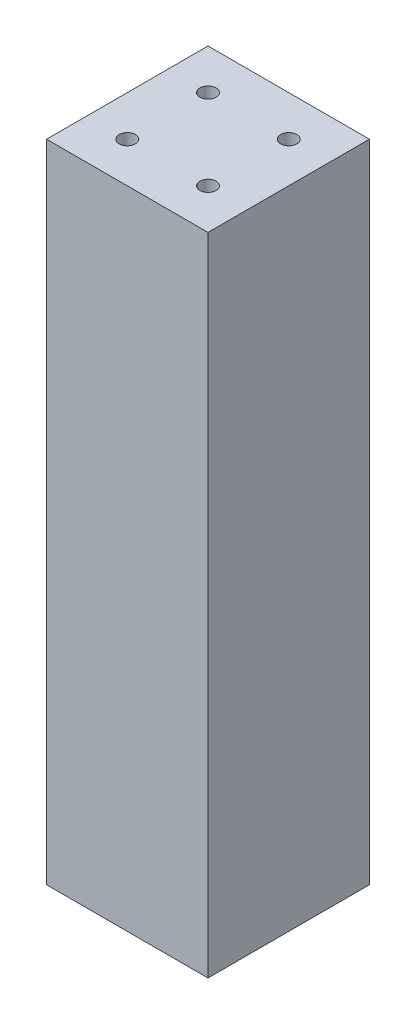
SolidWorks part; units mm, degrees
ref_plane "Front Plane" through (0, 0, 0) normal (0, 0, 1) x (1, 0, 0)
ref_plane "Top Plane" through (0, 0, 0) normal (0, 1, 0) x (1, 0, 0)
ref_plane "Right Plane" through (0, 0, 0) normal (1, 0, 0) x (0, 0, -1)
sketch "Sketch1" plane through (0, 0, 0) normal (0, 1, 0) x (1, 0, 0)
  line L1 (-25.4, -25.4) -> (25.4, -25.4)
  line L2 (-25.4, -25.4) -> (-25.4, 25.4)
  line L3 (-25.4, 25.4) -> (25.4, 25.4)
  line L4 (25.4, -25.4) -> (25.4, 25.4)
  line L5 (0, 25.4) -> (0, -25.4) construction
  line L6 (-25.4, 0) -> (25.4, 0) construction
  point P0 (0, 0)
  dimension "D1" = 50.8
  dimension "D2" = 50.8
extrude "Boss-Extrude1" add sketch "Sketch1" along normal blind 203.2
hole_wizard "1/4-20 Tapped Hole1" positions "Sketch2" profile "Sketch4" tap size "1/4-20" standard "ANSI Inch"
sketch "Sketch2" plane through (0, 203.2, 0) normal (0, 1, 0) x (1, 0, 0)
  line L0 (25.4, 25.4) -> (-25.4, 25.4) construction
  line L1 (-25.4, 25.4) -> (-25.4, -25.4) construction
  point P0 (-12.7, 12.7)
  point P9 (12.7, 12.7)
  point P11 (12.7, -12.7)
  point P13 (-12.7, -12.7)
  dimension "D1" = 12.7
  dimension "D2" = 12.7
  dimension "D3" = 25.4
  dimension "D4" = 25.4
sketch "Sketch4" plane through (-12.7, 203.2, -12.7) normal (1, 0, 0) x (0, 0, 1)
  line L0 (0, 0) -> (0, 18.0438)
  line L1 (0, 18.0438) -> (2.5527, 16.51)
  line L2 (2.5527, 16.51) -> (2.5527, 0)
  line L5 (2.5527, 0) -> (0, 0)
  line L10 (0, 18.0438) -> (-2.5527, 16.51) construction
  line L11 (0, -6.35) -> (0, 107.95) construction
  dimension "Tap Drill Dia." = 5.1054
  dimension "Tap Drill Depth" = 16.51
  dimension "Drill Angle" = 118
cosmetic thread "Hole Thread1" parameters "D1"=12.7, "D2"=6.35
cosmetic thread "Hole Thread2" parameters "D1"=12.7, "D2"=6.35
cosmetic thread "Hole Thread3" parameters "D1"=12.7, "D2"=6.35
cosmetic thread "Hole Thread4" parameters "D1"=12.7, "D2"=6.35
hole_wizard "1/4-20 Tapped Hole2" positions "Sketch5" profile "Sketch6" tap size "1/4-20" standard "ANSI Inch"
sketch "Sketch5" plane through (0, 0, 0) normal (0, -1, 0) x (-1, 0, 0)
  line L0 (25.4, 25.4) -> (25.4, -25.4) construction
  line L2 (-25.4, 25.4) -> (25.4, 25.4) construction
  point P0 (-12.7, 12.7)
  point P2 (12.7, 12.7)
  point P4 (12.7, -12.7)
  point P6 (-12.7, -12.7)
  dimension "D1" = 12.7
  dimension "D2" = 12.7
  dimension "D3" = 25.4
  dimension "D4" = 25.4
sketch "Sketch6" plane through (12.7, 0, -12.7) normal (1, 0, 0) x (0, 0, -1)
  line L0 (0, 0) -> (0, 18.0438)
  line L1 (0, 18.0438) -> (2.5527, 16.51)
  line L2 (2.5527, 16.51) -> (2.5527, 0)
  line L5 (2.5527, 0) -> (0, 0)
  line L10 (0, 18.0438) -> (-2.5527, 16.51) construction
  line L11 (0, -6.35) -> (0, 107.95) construction
  dimension "Tap Drill Dia." = 5.1054
  dimension "Tap Drill Depth" = 16.51
  dimension "Drill Angle" = 118
cosmetic thread "Hole Thread5" parameters "D1"=12.7, "D2"=6.35
cosmetic thread "Hole Thread6" parameters "D1"=12.7, "D2"=6.35
cosmetic thread "Hole Thread7" parameters "D1"=12.7, "D2"=6.35
cosmetic thread "Hole Thread8" parameters "D1"=12.7, "D2"=6.35
